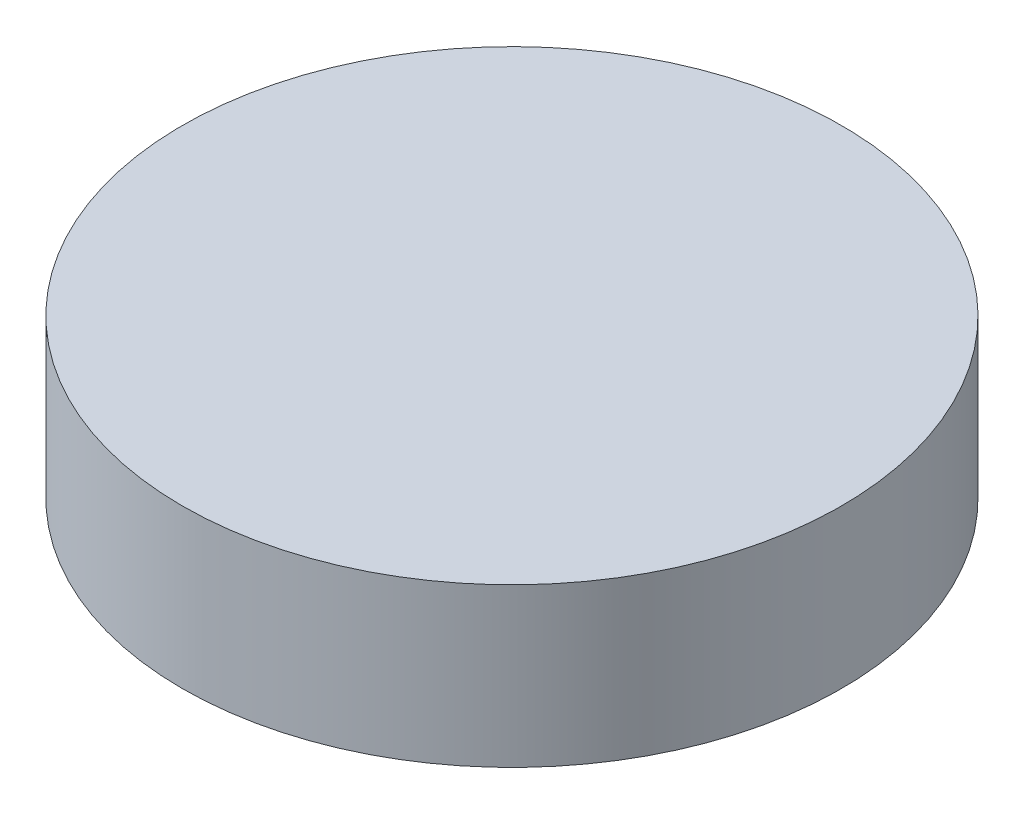
SolidWorks part; units mm, degrees
ref_plane "Front Plane" through (0, 0, 0) normal (0, 0, 1) x (1, 0, 0)
ref_plane "Top Plane" through (0, 0, 0) normal (0, 1, 0) x (1, 0, 0)
ref_plane "Right Plane" through (0, 0, 0) normal (1, 0, 0) x (0, 0, -1)
other "Configuration Table"
sketch "Sketch1" plane through (0, 0, 0) normal (0, 1, 0) x (1, 0, 0)
  circle A0 centre (50, 50) radius 25
extrude "TOPPING_ayar_ayagi_1" add sketch "Sketch1" along normal blind 12 separate body
